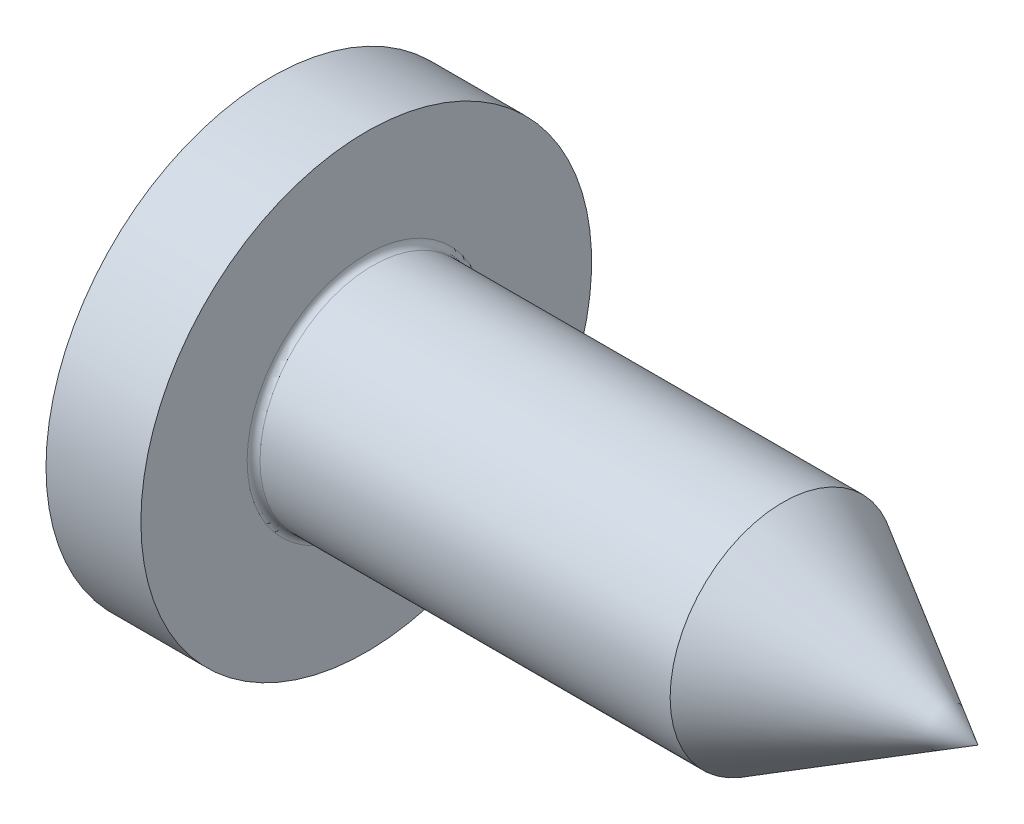
SolidWorks part; units mm, degrees
ref_plane "Front Plane" through (0, 0, 0) normal (0, 0, 1) x (1, 0, 0)
ref_plane "Top Plane" through (0, 0, 0) normal (0, 1, 0) x (1, 0, 0)
ref_plane "Right Plane" through (0, 0, 0) normal (1, 0, 0) x (0, 0, -1)
sketch "Sketch1" plane through (0, 0, 0) normal (0, 0, 1) x (1, 0, 0)
  line L0 (0, 0) -> (5.2282, 0) construction
  line L2 (0, 3.5) -> (-1.4734, 3.5)
  line L3 (-2.6, 0) -> (-2.6, -0.7496) construction
  line L4 (-2.6, 0) -> (9.5, 0)
  line L5 (0, 1.75) -> (9.5, 1.75)
  line L6 (9.5, 1.75) -> (9.5, 0)
  line L7 (0, 1.75) -> (0, 3.5)
  arc A0 (-1.4734, 3.5) -> (-2.6, 0) centre (3.4, 0) ccw
  dimension "rf" = 6
  dimension "Dk" = 7
  dimension "K" = 2.6
  dimension "d" = 3.5
  dimension "l" = 9.5
revolve "Revolve1" add sketch "Sketch1" angle 360 about L0
cosmetic thread "ThreadCosmetic" [suppressed] parameters "D1"=9.15, "D2"=2.64
chamfer "Chamfer1" distance 0.35 angle 60 1 edges at (9.5, 0, 1.75)
sketch "Sketch5" plane through (0, 0, 0) normal (0, 0, 1) x (1, 0, 0)
  line L0 (1.1817, 1.32) -> (0.3783, 1.32)
  line L1 (0.3783, 1.32) -> (0.13, 1.75)
  line L2 (1.1817, 1.32) -> (1.43, 1.75)
  line L3 (0.13, 1.75) -> (0.13, 2)
  line L4 (1.43, 1.75) -> (1.43, 2)
  line L5 (0.13, 2) -> (1.43, 2)
  line L6 (0.78, 1.32) -> (0.78, 0) construction
  line L7 (0, 0) -> (7.3035, 0) construction
  line L9 (8.8938, 1.75) -> (0, 1.75) construction
  line L12 (0, -1.75) -> (0, 1.75) construction
  dimension "D2" = 60
  dimension "D3" = 0.25
  dimension "advance" = 1.3
  dimension "minordia" = 2.64
  dimension "threadstart" = 0.78
revolve "ThreadSchematic" [suppressed] cut sketch "Sketch5" angle 360 about L7
pattern_linear "ThdSchPat" [suppressed] count 8 spacing 1.3 along (1, 0, 0)
sketch "Sketch2" plane through (0, 0, 0) normal (0, 0, 1) x (1, 0, 0)
  line L0 (0, 0) -> (5.7679, 0) construction
  line L1 (9.5, 0) -> (6.4689, 1.75)
  line L3 (9.5, 1.75) -> (9.5, 0) construction
  line L4 (6.4689, 1.75) -> (6.4689, 1.85)
  line L5 (6.4689, 1.85) -> (9.6, 1.85)
  line L6 (9.6, 1.85) -> (9.6, 0)
  line L7 (9.6, 0) -> (9.5, 0)
  point P9 (0, 1.75)
  dimension "D1" = 30
  dimension "D2" = 0.1
  dimension "D3" = 0.1
revolve "EndCone" cut sketch "Sketch2" angle 360 about L0
ref_plane "Plane4" through (-2.6, 0, 0) normal (1, 0, 0) x (0, 0, -1)
sketch "Sketch3" plane through (-2.6, 0, 0) normal (1, 0, 0) x (0, 0, -1)
  line L0 (0, 2.343) -> (0, -2.4842) construction
  line L1 (2.7661, 0) -> (-3.4558, 0) construction
  line L2 (-0.4875, 1.95) -> (0.4875, 1.95)
  line L3 (0.4875, 1.95) -> (0.2925, 1.17)
  line L4 (0, 0) -> (1.9578, 1.9578) construction
  line L5 (0.2925, 1.17) -> (0.6137, 0.6137)
  line L6 (0.2925, 1.17) -> (0, 0) construction
  line L7 (-0.2925, 1.17) -> (-0.6137, 0.6137)
  line L8 (-0.4875, 1.95) -> (-0.2925, 1.17)
  line L9 (1.95, 0.4875) -> (1.95, -0.4875)
  line L10 (1.95, -0.4875) -> (1.17, -0.2925)
  line L11 (1.17, -0.2925) -> (0.6137, -0.6137)
  line L12 (1.17, 0.2925) -> (0.6137, 0.6137)
  line L13 (1.95, 0.4875) -> (1.17, 0.2925)
  line L14 (0.4875, -1.95) -> (-0.4875, -1.95)
  line L15 (-0.4875, -1.95) -> (-0.2925, -1.17)
  line L16 (-0.2925, -1.17) -> (-0.6137, -0.6137)
  line L17 (0.2925, -1.17) -> (0.6137, -0.6137)
  line L18 (0.4875, -1.95) -> (0.2925, -1.17)
  line L19 (-1.95, -0.4875) -> (-1.95, 0.4875)
  line L20 (-1.95, 0.4875) -> (-1.17, 0.2925)
  line L21 (-1.17, 0.2925) -> (-0.6137, 0.6137)
  line L22 (-1.17, -0.2925) -> (-0.6137, -0.6137)
  line L23 (-1.95, -0.4875) -> (-1.17, -0.2925)
  point P14 (0, 1.95)
  point P23 (1.95, 0)
  point P30 (0, -1.95)
  point P37 (-1.95, 0)
  dimension "D1" = 45
  dimension "m" = 3.9
  dimension "D3" = 0.975
  dimension "D4" = 75
  dimension "D5" = 2.34
extrude "Cut-Extrude1" cut sketch "Sketch3" along normal blind 1.4 draft 6
sketch "Sketch4" plane through (-2.6, 0, 0) normal (1, 0, 0) x (0, 0, -1)
  line L0 (0, 2.1951) -> (0, -2.1951) construction
  line L1 (2.1996, 0) -> (-2.3835, 0) construction
  line L2 (-1.7236, -1.7236) -> (1.7236, 1.7236) construction
  line L3 (1.95, 0.4875) -> (-1.95, 0.4875)
  line L4 (1.95, 0.4875) -> (1.95, -0.4875)
  line L5 (1.95, -0.4875) -> (-1.95, -0.4875)
  line L6 (-1.95, 0.4875) -> (-1.95, -0.4875)
  line L7 (0.4875, 1.95) -> (-0.4875, 1.95)
  line L8 (0.4875, 1.95) -> (0.4875, -1.95)
  line L9 (0.4875, -1.95) -> (-0.4875, -1.95)
  line L10 (-0.4875, 1.95) -> (-0.4875, -1.95)
  line L11 (1.7236, 1.7236) -> (0.7921, 0.4875)
  line L12 (1.7236, 1.7236) -> (0.4875, 0.7921)
  line L13 (0.4875, 0.7921) -> (-0.4875, 0.7921) construction
  line L14 (0, 0) -> (-1.7236, 1.7236) construction
  line L15 (-1.7236, -1.7236) -> (-0.4875, -0.7921)
  line L16 (-1.7236, -1.7236) -> (-0.7921, -0.4875)
  line L17 (-0.4875, 0.7921) -> (-1.7236, 1.7236)
  line L18 (-1.7236, 1.7236) -> (-0.7921, 0.4875)
  line L19 (-0.7921, -0.4875) -> (-0.7921, 0.4875) construction
  line L20 (0.7921, -0.4875) -> (1.7236, -1.7236)
  line L21 (1.7236, -1.7236) -> (0.4875, -0.7921)
  circle A0 centre (0, 0) radius 2.4375 construction
  dimension "m" = 3.9
  dimension "D1" = 4.875
  dimension "D2" = 0.975
  dimension "D3" = 45
  dimension "D4" = 8
  dimension "D5" = 45
extrude "TypeZ" [suppressed] cut sketch "Sketch4" along normal blind 1.3
fillet "Fillet1" radius 0.1 1 edges at (0, 0, 1.75)
equation "\"D1@Chamfer1\" = \"d@Sketch1\"/10"
equation "\"D1@ThreadCosmetic\" = \"l@Sketch1\" - \"D1@Chamfer1\""
equation "\"minordia@Sketch5\" = \"D2@ThreadCosmetic\""
equation "\"D1@Plane4\" = \"K@Sketch1\""
equation "\"D5@Sketch3\" = \"m@Sketch3\" * 3 / 5"
equation "\"D3@Sketch3\" = \"m@Sketch3\" / 4"
equation "\"m@Sketch4\" = \"m@Sketch3\""
equation "\"D2@Sketch4\" =  \"m@Sketch4\" / 4"
equation "\"D1@TypeZ\" = \"K@Sketch1\" / 2"
equation "\"D1@Sketch4\" = \"m@Sketch4\" * 5 / 4"
equation "\"threadstart@Sketch5\" = \"advance@Sketch5\"*0.6"
equation "\"D1@ThdSchPat\" = int((\"l@Sketch1\"/\"advance@Sketch5\") + 0.8)"
equation "\"D3@ThdSchPat\" = \"advance@Sketch5\""
